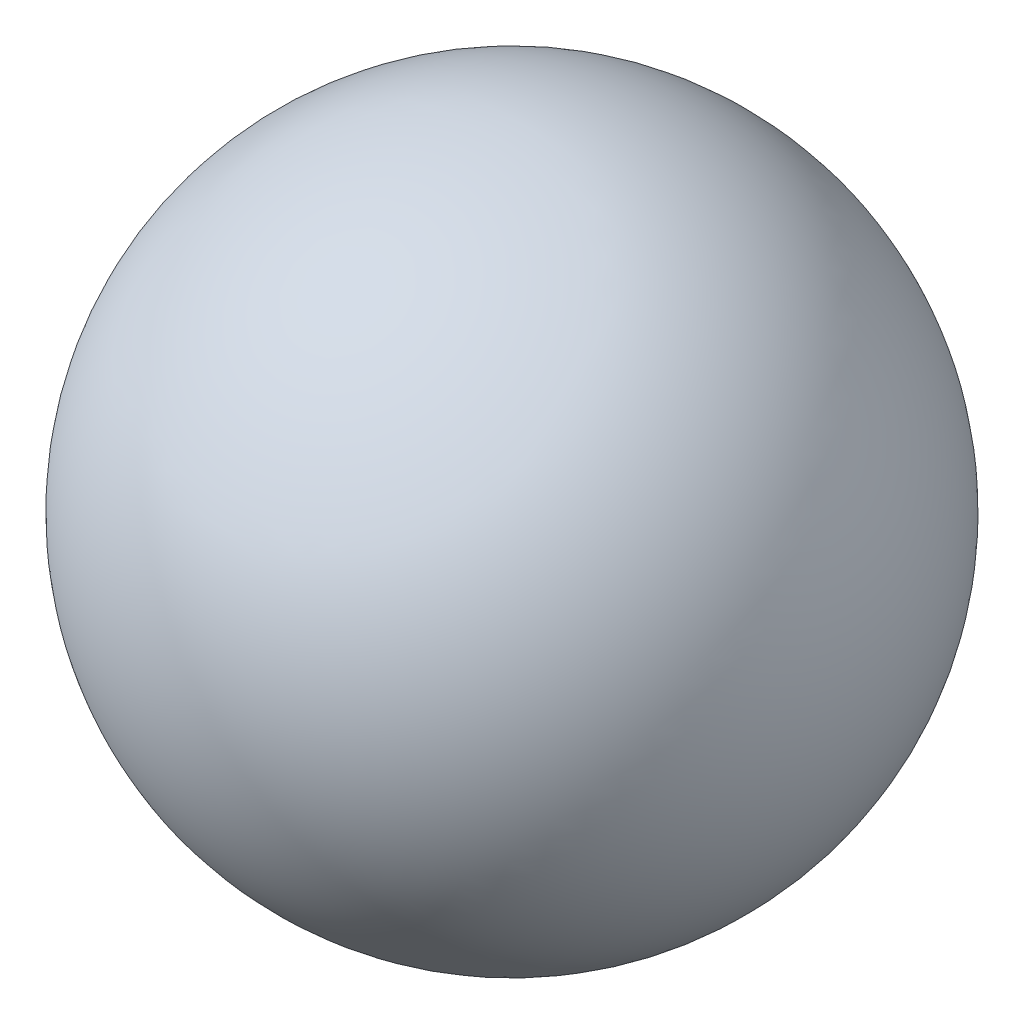
SolidWorks part; units mm, degrees
ref_plane "Front Plane" through (0, 0, 0) normal (0, 0, 1) x (1, 0, 0)
ref_plane "Top Plane" through (0, 0, 0) normal (0, 1, 0) x (1, 0, 0)
ref_plane "Right Plane" through (0, 0, 0) normal (1, 0, 0) x (0, 0, -1)
sketch "Sketch1" plane through (0, 0, 0) normal (1, 0, 0) x (0, 0, -1)
  line L0 (-12, 0) -> (12, 0)
  arc A3 (12, 0) -> (-12, 0) centre (0, 0) cw
  dimension "D1" = 24
revolve "Revolve1" add sketch "Sketch1" angle 360 about L0
